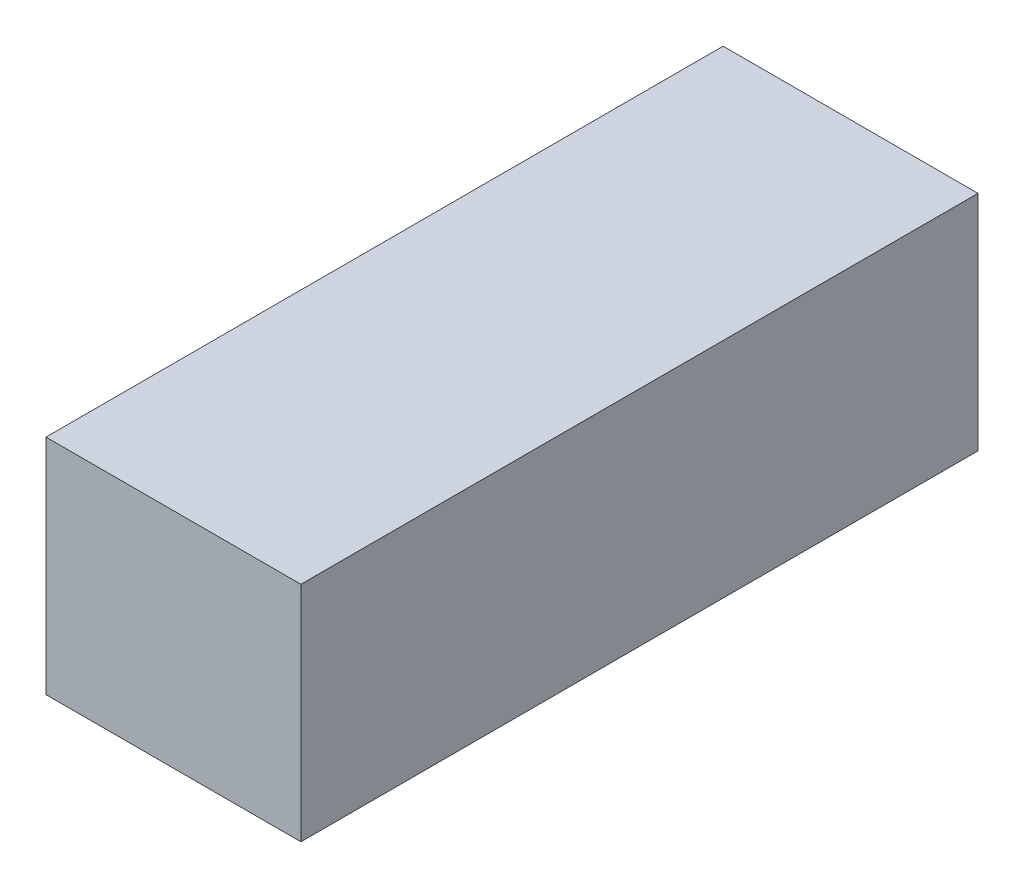
SolidWorks part; units mm, degrees
ref_plane "Front Plane" through (0, 0, 0) normal (0, 0, 1) x (1, 0, 0)
ref_plane "Top Plane" through (0, 0, 0) normal (0, 1, 0) x (1, 0, 0)
ref_plane "Right Plane" through (0, 0, 0) normal (1, 0, 0) x (0, 0, -1)
sketch "Sketch1" plane through (0, 0, 0) normal (0, 0, 1) x (1, 0, 0)
  line L1 (0, 0) -> (50.8, 0)
  line L2 (0, 0) -> (0, 44.45)
  line L3 (0, 44.45) -> (50.8, 44.45)
  line L4 (50.8, 0) -> (50.8, 44.45)
  dimension "D1" = 44.45
  dimension "D2" = 50.8
extrude "Boss-Extrude1" add sketch "Sketch1" along normal blind 134.9375
